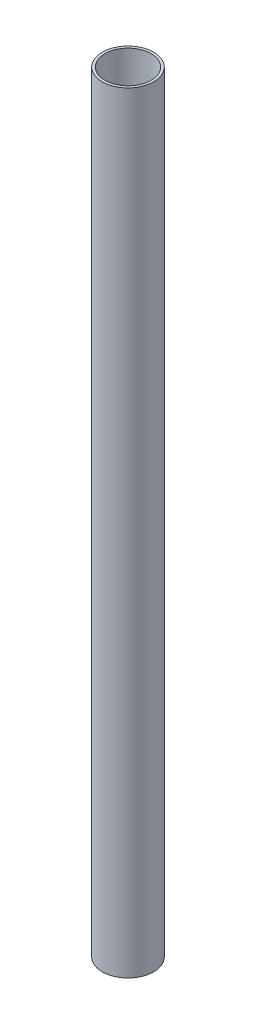
SolidWorks part; units mm, degrees
ref_plane "前视基准面" through (0, 0, 0) normal (0, 0, 1) x (1, 0, 0)
ref_plane "上视基准面" through (0, 0, 0) normal (0, 1, 0) x (1, 0, 0)
ref_plane "右视基准面" through (0, 0, 0) normal (1, 0, 0) x (0, 0, -1)
sketch "草图1" plane through (0, 0, 0) normal (0, 1, 0) x (1, 0, 0)
  circle A0 centre (0, 0) radius 10
  dimension "D1" = 20
extrude "1mm" add sketch "草图1" along normal mid plane 300 thin thin type one direction reverse wall 1
